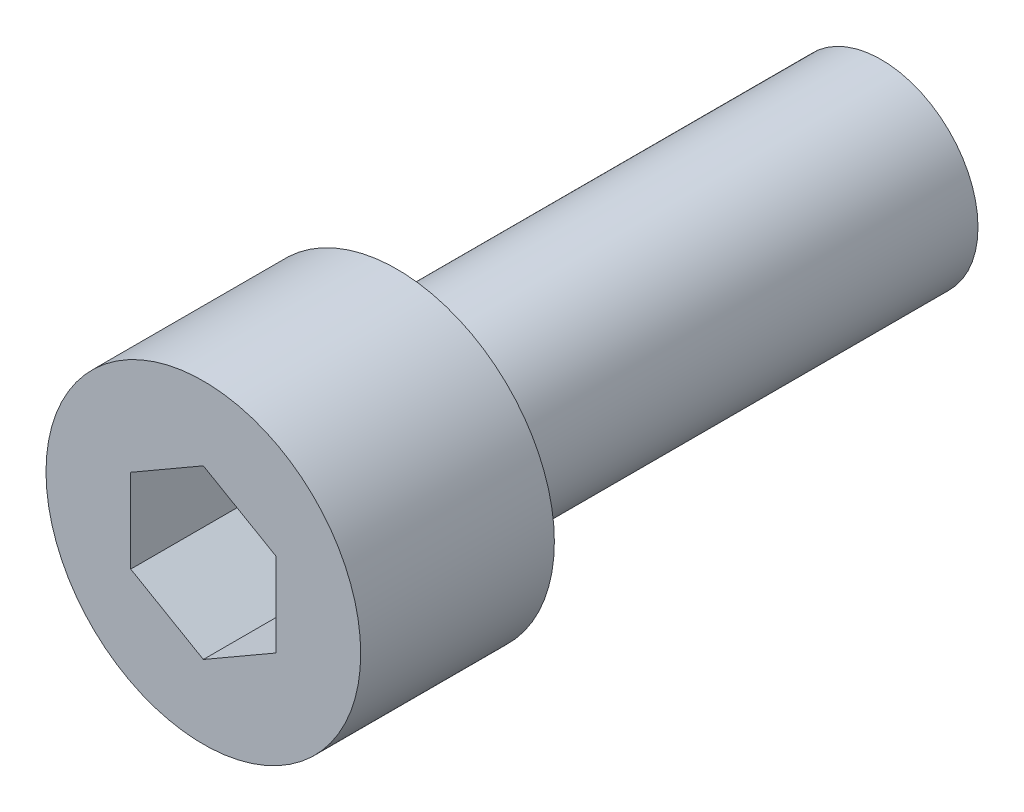
SolidWorks part; units mm, degrees
ref_plane "Płaszczyzna przednia" through (0, 0, 0) normal (0, 0, 1) x (1, 0, 0)
ref_plane "Płaszczyzna górna" through (0, 0, 0) normal (0, 1, 0) x (1, 0, 0)
ref_plane "Płaszczyzna prawa" through (0, 0, 0) normal (1, 0, 0) x (0, 0, -1)
sketch "Szkic1" plane through (0, 0, 0) normal (1, 0, 0) x (0, 0, -1)
  line L0 (0, 0) -> (30.4213, 0) construction
  line L1 (0, 0) -> (0, 6.5)
  line L2 (0, 6.5) -> (8, 6.5)
  line L3 (8, 6.5) -> (8, 4)
  line L4 (8, 4) -> (28, 4)
  line L5 (28, 4) -> (28, 0)
  line L6 (28, 0) -> (0, 0)
  dimension "D1" = 13
  dimension "D2" = 8
  dimension "D3" = 8
  dimension "D4" = 20
revolve "Obrót1" add sketch "Szkic1" angle 360 about L0
sketch "Szkic2" plane through (0, 0, 0) normal (0, 0, 1) x (1, 0, 0)
  line L1 (-3, -1.7321) -> (0, -3.4641)
  line L2 (0, -3.4641) -> (3, -1.7321)
  line L3 (3, -1.7321) -> (3, 1.7321)
  line L4 (3, 1.7321) -> (0, 3.4641)
  line L5 (0, 3.4641) -> (-3, 1.7321)
  line L6 (-3, 1.7321) -> (-3, -1.7321)
  circle A0 centre (0, 0) radius 3 construction
  dimension "D1" = 6
extrude "Wytnij-wyciągnięcie1" cut sketch "Szkic2" against normal blind 6
